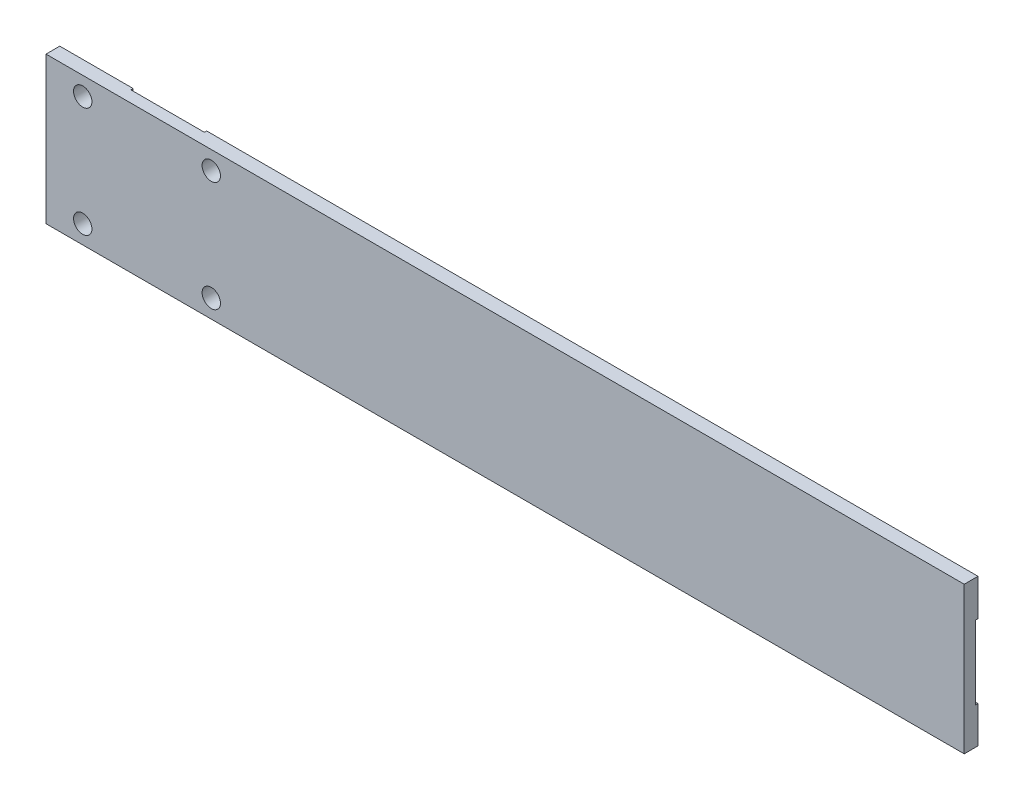
SolidWorks part; units mm, degrees
ref_plane "Front" through (0, 0, 0) normal (0, 0, 1) x (1, 0, 0)
ref_plane "Top" through (0, 0, 0) normal (0, 1, 0) x (1, 0, 0)
ref_plane "Right" through (0, 0, 0) normal (1, 0, 0) x (0, 0, -1)
sketch "Sketch1" plane through (0, 0, 0) normal (0, 0, 1) x (1, 0, 0)
  line L1 (0, 0) -> (635, 0)
  line L2 (0, 0) -> (0, 101.6)
  line L3 (0, 101.6) -> (635, 101.6)
  line L4 (635, 0) -> (635, 101.6)
  dimension "D1" = 101.6
  dimension "D2" = 635
extrude "Boss-Extrude1" add sketch "Sketch1" along normal blind 9.525
sketch "Sketch2" plane through (0, 0, 0) normal (1, 0, 0) x (0, 0, -1)
  line L0 (0, 0) -> (0, 101.6) construction
  line L1 (0, 76.2) -> (-1.5875, 76.2)
  line L2 (0, 76.2) -> (0, 25.4)
  line L3 (0, 25.4) -> (-1.5875, 25.4)
  line L4 (-1.5875, 76.2) -> (-1.5875, 25.4)
  line L5 (-9.525, 101.6) -> (0, 101.6) construction
  dimension "D1" = 25.4
  dimension "D2" = 50.8
  dimension "D3" = 1.5875
extrude "Cut-Extrude1" cut sketch "Sketch2" against normal blind 9.525 and the other way through all from offset 60.325
sketch "Sketch3" plane through (0, 0, 0) normal (0, 0, -1) x (-1, 0, 0)
  line L0 (-635, 101.6) -> (0, 101.6) construction
  line L1 (0, 101.6) -> (0, 0) construction
  line L4 (18.8245, 50.8) -> (-106.6282, 50.8) construction
  circle A1 centre (-25.4, 88.9) radius 6.35
  circle A2 centre (-114.3, 88.9) radius 6.35
  circle A3 centre (-114.3, 12.7) radius 6.35
  circle A4 centre (-25.4, 12.7) radius 6.35
  dimension "D1" = 12.7
  dimension "D3" = 12.7
  dimension "D2" = 25.4
  dimension "D5" = 88.9
extrude "Cut-Extrude4" cut sketch "Sketch3" against normal through all both
sketch "Sketch5" plane through (0, 0, 0) normal (0, 0, -1) x (-1, 0, 0)
  line L0 (-635, 101.6) -> (0, 101.6) construction
  line L1 (-101.6, 101.6) -> (-50.8, 101.6)
  line L2 (-101.6, 101.6) -> (-101.6, 0)
  line L3 (-101.6, 0) -> (-50.8, 0)
  line L4 (-50.8, 101.6) -> (-50.8, 0)
  line L5 (0, 0) -> (-635, 0) construction
  line L6 (0, 101.6) -> (0, 0) construction
  dimension "D1" = 50.8
  dimension "D2" = 50.8
extrude "Cut-Extrude5" cut sketch "Sketch5" along direction (0, 0, -1) on the side against the normal up to surface (1.5875 mm away)
